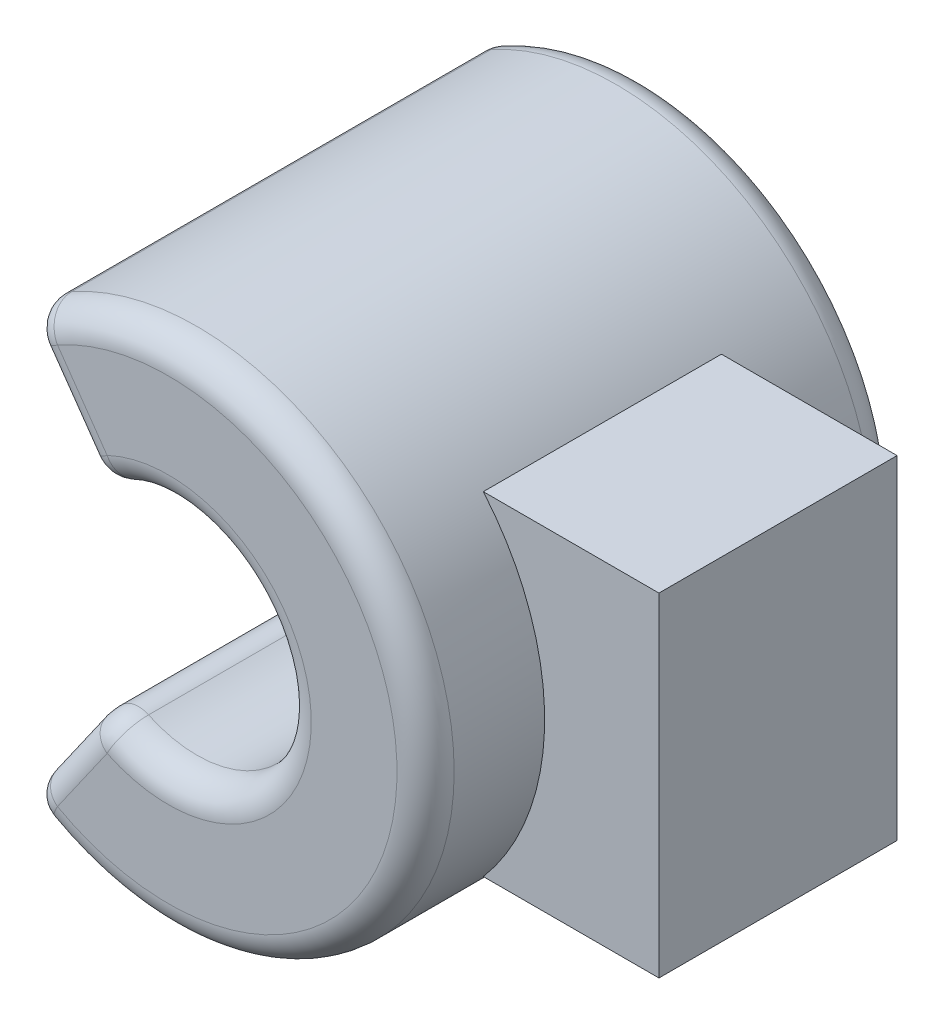
SolidWorks part; units mm, degrees
ref_plane "Front Plane" through (0, 0, 0) normal (0, 0, 1) x (1, 0, 0)
ref_plane "Top Plane" through (0, 0, 0) normal (0, 1, 0) x (1, 0, 0)
ref_plane "Right Plane" through (0, 0, 0) normal (1, 0, 0) x (0, 0, -1)
sketch "Sketch1" plane through (0, 0, 0) normal (0, 0, 1) x (1, 0, 0)
  line L0 (0, 0) -> (-1.3766, 1.966) construction
  line L1 (0, 0) -> (-1.3766, -1.966) construction
  line L2 (0, 0) -> (-24, 0) construction
  arc A0 (-1.3766, -1.966) -> (-1.3766, 1.966) centre (0, 0) ccw
  dimension "D1" = 110
  dimension "D2" = 55
extrude "Extrude-Thin1" add sketch "Sketch1" along normal mid plane 10 thin
fillet "Fillet1" radius 0.6 4 edges at (2.4, 0, -5) (2.4, 0, 5) (5.4, 0, -5) (5.4, 0, 5)
fillet "Fillet2" radius 0.5 16 edges at (-2.9965, 4.2795, 4.8243) (-2.9965, 4.2795, -4.8243) (-2.9965, -4.2795, 4.8243) (-2.9965, -4.2795, -4.8243) (-3.0973, 4.4234, 0) (-3.0973, -4.4234, 0) (-2.2369, 3.1947, 5) (-1.4774, 2.1099, 4.8243) (-1.3766, 1.966, 0) (-1.4774, 2.1099, -4.8243) (-2.2369, 3.1947, -5) (-2.2369, -3.1947, 5) (-1.4774, -2.1099, 4.8243) (-1.3766, -1.966, 0) (-1.4774, -2.1099, -4.8243) (-2.2369, -3.1947, -5)
sketch "Sketch2" plane through (0, 0, 0) normal (1, 0, 0) x (0, 0, -1)
  line L1 (-2.5, -3.5) -> (2.5, -3.5)
  line L2 (-2.5, -3.5) -> (-2.5, 3.5)
  line L3 (-2.5, 3.5) -> (2.5, 3.5)
  line L4 (2.5, -3.5) -> (2.5, 3.5)
  line L5 (-2.5, -3.5) -> (2.5, 3.5) construction
  line L6 (-2.5, 3.5) -> (2.5, -3.5) construction
  point P0 (0, 0)
  dimension "D1" = 5
  dimension "D2" = 7
extrude "Boss-Extrude1" add sketch "Sketch2" along normal blind 4 from offset 3.8
